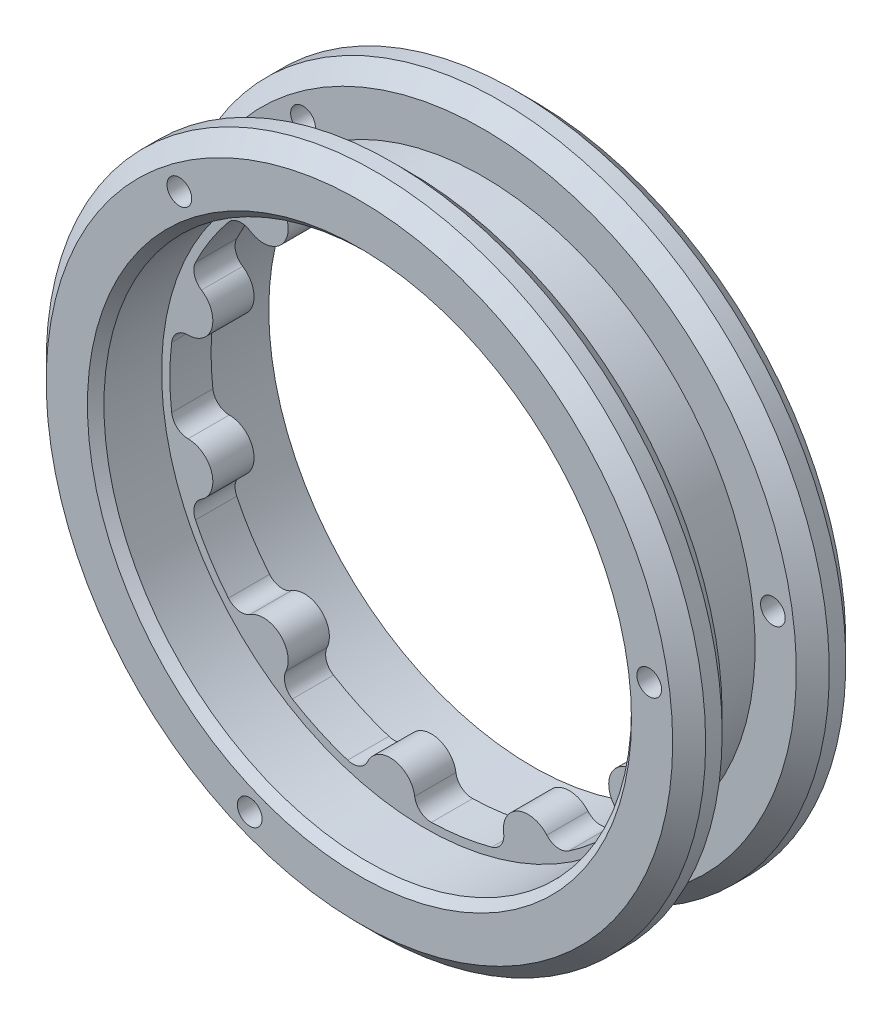
SolidWorks part; units mm, degrees
ref_plane "Front Plane" through (0, 0, 0) normal (0, 0, 1) x (1, 0, 0)
ref_plane "Top Plane" through (0, 0, 0) normal (0, 1, 0) x (1, 0, 0)
ref_plane "Right Plane" through (0, 0, 0) normal (1, 0, 0) x (0, 0, -1)
other "Configuration Table"
sketch "草图1" plane through (0, 0, 13.6167) normal (0, 0, 1) x (1, 0, 0)
  line L0 (0.1738, -3.1409) -> (15.1738, -3.1409) construction
  arc A0 (-4.5411, 11.6246) -> (-7.8977, 10.0917) centre (0.1738, -3.1409) ccw
  circle A1 centre (0.1738, -3.1409) radius 16.5
  arc A10 (-3.3265, 11.0857) -> (-0.4758, 11.4956) centre (-1.961, 11.7064) ccw
  arc A13 (0.5377, 12.3548) -> (-0.4758, 11.4956) centre (0.5142, 11.3551) ccw
  arc A14 (-3.3265, 11.0857) -> (-4.5411, 11.6246) centre (-4.2369, 10.672) ccw
  arc A15 (4.9206, 10.7197) -> (4.1902, 11.8297) centre (3.9311, 10.8638) ccw
  arc A16 (4.9206, 10.7197) -> (7.5404, 9.5233) centre (6.405, 10.5036) ccw
  arc A17 (8.8576, 9.6982) -> (7.5404, 9.5233) centre (8.2973, 8.8698) ccw
  arc A18 (11.6607, 5.953) -> (11.6463, 7.2817) centre (10.9062, 6.6093) ccw
  arc A19 (11.6607, 5.953) -> (13.2178, 3.5302) centre (12.7926, 4.9687) ccw
  arc A20 (14.4204, 2.9652) -> (13.2178, 3.5302) centre (13.5012, 2.5712) ccw
  arc A21 (14.7538, -1.7009) -> (15.46, -0.5754) centre (14.4738, -0.7409) ccw
  arc A22 (14.7538, -1.7009) -> (14.7538, -4.5809) centre (15.1738, -3.1409) ccw
  arc A23 (15.46, -5.7064) -> (14.7538, -4.5809) centre (14.4738, -5.5409) ccw
  arc A24 (13.2178, -9.8121) -> (14.4204, -9.247) centre (13.5012, -8.8531) ccw
  arc A25 (13.2178, -9.8121) -> (11.6607, -12.2349) centre (12.7926, -11.2505) ccw
  arc A26 (11.6463, -13.5635) -> (11.6607, -12.2349) centre (10.9062, -12.8911) ccw
  arc A27 (7.5404, -15.8052) -> (8.8576, -15.98) centre (8.2973, -15.1517) ccw
  arc A28 (7.5404, -15.8052) -> (4.9206, -17.0015) centre (6.405, -16.7854) ccw
  arc A29 (4.1902, -18.1115) -> (4.9206, -17.0015) centre (3.9311, -17.1457) ccw
  arc A30 (-0.4758, -17.7774) -> (0.5377, -18.6366) centre (0.5142, -17.6369) ccw
  arc A31 (-0.4758, -17.7774) -> (-3.3265, -17.3676) centre (-1.961, -17.9882) ccw
  arc A32 (-4.5411, -17.9064) -> (-3.3265, -17.3676) centre (-4.2369, -16.9538) ccw
  arc A33 (-8.2858, -15.1027) -> (-7.8977, -16.3735) centre (-7.3769, -15.5198) ccw
  arc A34 (-8.2858, -15.1027) -> (-10.4624, -13.2167) centre (-9.6491, -14.4772) ccw
  arc A35 (-11.7755, -13.0134) -> (-10.4624, -13.2167) centre (-11.0045, -12.3765) ccw
  arc A36 (-13.4099, -8.6302) -> (-13.7705, -9.9091) centre (-12.8708, -9.4725) ccw
  arc A37 (-13.4099, -8.6302) -> (-14.2213, -5.8669) centre (-14.2186, -7.3669) ccw
  arc A38 (-15.216, -4.9859) -> (-14.2213, -5.8669) centre (-14.2231, -4.8669) ccw
  arc A39 (-14.2213, -0.4149) -> (-15.216, -1.2959) centre (-14.2231, -1.4149) ccw
  arc A40 (-14.2213, -0.4149) -> (-13.4099, 2.3484) centre (-14.2186, 1.0851) ccw
  arc A41 (-13.7705, 3.6273) -> (-13.4099, 2.3484) centre (-12.8708, 3.1906) ccw
  arc A42 (-10.4624, 6.9349) -> (-11.7755, 6.7316) centre (-11.0045, 6.0946) ccw
  arc A43 (-10.4624, 6.9349) -> (-8.2858, 8.8209) centre (-9.6491, 8.1953) ccw
  arc A44 (-7.8977, 10.0917) -> (-8.2858, 8.8209) centre (-7.3769, 9.238) ccw
  arc A45 (-11.7755, 6.7316) -> (-13.7705, 3.6273) centre (0.1738, -3.1409) ccw
  arc A46 (-15.216, -1.2959) -> (-15.216, -4.9859) centre (0.1738, -3.1409) ccw
  arc A47 (-13.7705, -9.9091) -> (-11.7755, -13.0134) centre (0.1738, -3.1409) ccw
  arc A48 (-7.8977, -16.3735) -> (-4.5411, -17.9064) centre (0.1738, -3.1409) ccw
  arc A49 (0.5377, -18.6366) -> (4.1902, -18.1115) centre (0.1738, -3.1409) ccw
  arc A50 (8.8576, -15.98) -> (11.6463, -13.5635) centre (0.1738, -3.1409) ccw
  arc A51 (14.4204, -9.247) -> (15.46, -5.7064) centre (0.1738, -3.1409) ccw
  arc A52 (15.46, -0.5754) -> (14.4204, 2.9652) centre (0.1738, -3.1409) ccw
  arc A53 (11.6463, 7.2817) -> (8.8576, 9.6982) centre (0.1738, -3.1409) ccw
  arc A54 (4.1902, 11.8297) -> (0.5377, 12.3548) centre (0.1738, -3.1409) ccw
  point P29 (0.1738, -3.1409)
  point P85 (0.1738, -3.1409)
  dimension "D1" = 11
extrude "凸台-拉伸1" add sketch "草图1" along normal blind 6.5
sketch "草图2" plane through (0, 0, 13.6167) normal (0, 0, -1) x (-1, 0, 0)
  circle A0 centre (-0.1738, -3.1409) radius 16 construction
  circle A1 centre (-0.1738, -3.1409) radius 16.5 construction
  circle A2 centre (-0.1738, -3.1409) radius 16
  circle A3 centre (-0.1738, -3.1409) radius 16.5
extrude "凸台-拉伸2" add sketch "草图2" along normal blind 4
sketch "草图4" plane through (0, 0, 20.1167) normal (0, 0, 1) x (1, 0, 0)
  circle A0 centre (0.1738, -3.1409) radius 16
extrude "切除-拉伸2" cut sketch "草图4" against normal blind 4
sketch "草图5" plane through (0, 0, 9.6167) normal (0, 0, -1) x (-1, 0, 0)
  circle A0 centre (-0.1738, -3.1409) radius 16.5
  circle A1 centre (-0.1738, -3.1409) radius 20
extrude "凸台-拉伸3" add sketch "草图5" against normal blind 3
sketch "草图6" plane through (0, 0, 20.1167) normal (0, 0, 1) x (1, 0, 0)
  circle A0 centre (0.1738, -3.1409) radius 16.5
  circle A1 centre (0.1738, -3.1409) radius 20
extrude "凸台-拉伸4" add sketch "草图6" against normal blind 3
chamfer "倒角1" distance 1 angle 45 4 edges at (20.1738, -3.1409, 17.1167) (-19.8262, -3.1409, 12.6167) (-19.8262, -3.1409, 9.6167) (20.1738, -3.1409, 20.1167)
sketch "草图7" plane through (0, 0, 20.1167) normal (0, 0, 1) x (1, 0, 0)
  circle A0 centre (17.7509, -0.6757) radius 0.75
  dimension "D1" = 1.5
extrude "切除-拉伸3" cut sketch "草图7" against normal through all
pattern_circular "阵列(圆周)1" count 3 every 120 about axis through (0.1738, -3.1409, 0) along (0, 0, 1) of "切除-拉伸3"
chamfer "倒角2" distance 0.5 angle 45 1 edges at (16.1738, -3.1409, 20.1167)
